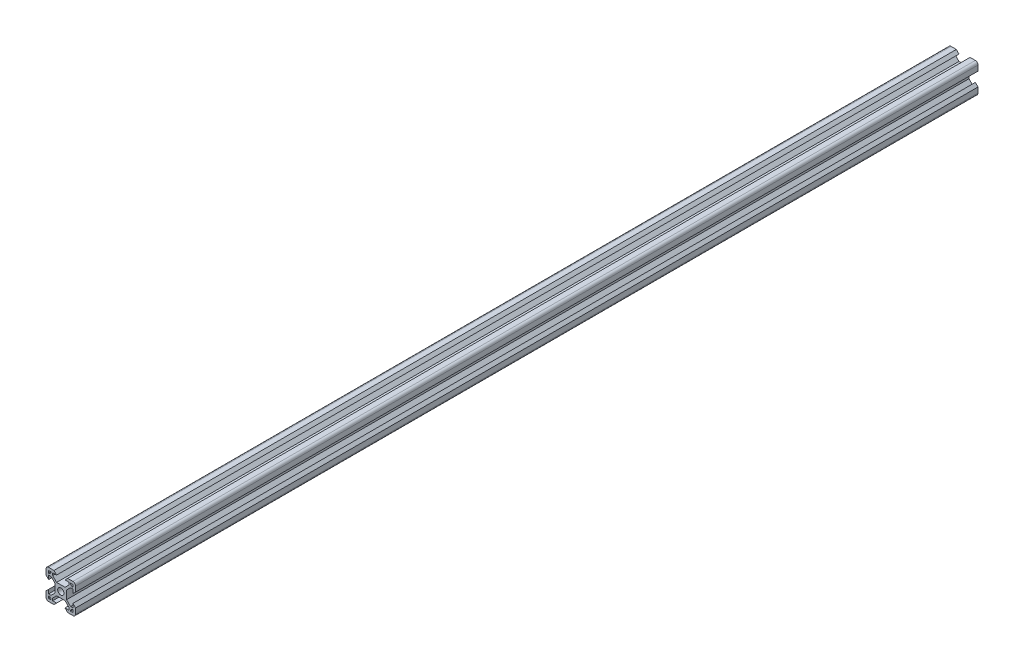
SolidWorks part; units mm, degrees
material "6063-T5"
ref_plane "Plane1" through (0, 0, 0) normal (0, 0, 1) x (1, 0, 0)
ref_plane "Plane2" through (0, 0, 0) normal (0, 1, 0) x (1, 0, 0)
ref_plane "Plane3" through (0, 0, 0) normal (1, 0, 0) x (0, 0, -1)
sketch "Sketch1" plane through (0, 0, 0) normal (0, 0, 1) x (1, 0, 0)
  line L0 (-3.9007, 0) -> (-3.9007, -2.84)
  line L1 (-3.9007, -2.84) -> (-6.56, -5.4993)
  line L2 (-6.56, -5.4993) -> (-8.2, -5.4993)
  line L3 (-8.2, -5.4993) -> (-8.2, -2.84)
  line L4 (-8.2, -2.84) -> (-10, -4.64)
  line L5 (-10, -4.64) -> (-10, -8.2)
  line L6 (0, 0) -> (-17.0509, -17.0509) construction
  line L7 (0, 0) -> (0, -17.0509) construction
  line L8 (0, 0) -> (-30.3777, 0) construction
  line L9 (-4.64, -10) -> (-8.2, -10)
  line L10 (-2.84, -8.2) -> (-4.64, -10)
  line L11 (-5.4993, -8.2) -> (-2.84, -8.2)
  line L12 (-5.4993, -6.56) -> (-5.4993, -8.2)
  line L13 (-2.84, -3.9007) -> (-5.4993, -6.56)
  line L14 (0, -3.9007) -> (-2.84, -3.9007)
  line L15 (-8.2, -8.2) -> (-8.2, -6.5693)
  line L16 (-8.2, -6.5693) -> (-7.63, -6.5693)
  line L17 (-7.63, -6.5693) -> (-6.5693, -7.63)
  line L18 (-6.5693, -7.63) -> (-6.5693, -8.2)
  line L19 (-6.5693, -8.2) -> (-8.2, -8.2)
  line L20 (-3.9007, 0) -> (-3.9007, 2.84)
  line L21 (-3.9007, 2.84) -> (-6.56, 5.4993)
  line L22 (-6.56, 5.4993) -> (-8.2, 5.4993)
  line L23 (-8.2, 5.4993) -> (-8.2, 2.84)
  line L24 (-8.2, 2.84) -> (-10, 4.64)
  line L25 (-10, 4.64) -> (-10, 8.2)
  line L26 (-4.64, 10) -> (-8.2, 10)
  line L27 (-2.84, 8.2) -> (-4.64, 10)
  line L28 (-5.4993, 8.2) -> (-2.84, 8.2)
  line L29 (-5.4993, 6.56) -> (-5.4993, 8.2)
  line L30 (-2.84, 3.9007) -> (-5.4993, 6.56)
  line L31 (0, 3.9007) -> (-2.84, 3.9007)
  line L32 (-8.2, 6.5693) -> (-8.2, 8.2)
  line L33 (-8.2, 8.2) -> (-6.5693, 8.2)
  line L34 (-6.5693, 8.2) -> (-6.5693, 7.63)
  line L35 (-6.5693, 7.63) -> (-7.63, 6.5693)
  line L36 (-7.63, 6.5693) -> (-8.2, 6.5693)
  line L37 (0, 3.9007) -> (2.84, 3.9007)
  line L38 (2.84, 3.9007) -> (5.4993, 6.56)
  line L39 (5.4993, 6.56) -> (5.4993, 8.2)
  line L40 (5.4993, 8.2) -> (2.84, 8.2)
  line L41 (2.84, 8.2) -> (4.64, 10)
  line L42 (4.64, 10) -> (8.2, 10)
  line L43 (10, 4.64) -> (10, 8.2)
  line L44 (8.2, 2.84) -> (10, 4.64)
  line L45 (8.2, 5.4993) -> (8.2, 2.84)
  line L46 (6.56, 5.4993) -> (8.2, 5.4993)
  line L47 (3.9007, 2.84) -> (6.56, 5.4993)
  line L48 (3.9007, 0) -> (3.9007, 2.84)
  line L49 (6.5693, 8.2) -> (8.2, 8.2)
  line L50 (8.2, 8.2) -> (8.2, 6.5693)
  line L51 (8.2, 6.5693) -> (7.63, 6.5693)
  line L52 (7.63, 6.5693) -> (6.5693, 7.63)
  line L53 (6.5693, 7.63) -> (6.5693, 8.2)
  line L54 (3.9007, 0) -> (3.9007, -2.84)
  line L55 (3.9007, -2.84) -> (6.56, -5.4993)
  line L56 (6.56, -5.4993) -> (8.2, -5.4993)
  line L57 (8.2, -5.4993) -> (8.2, -2.84)
  line L58 (8.2, -2.84) -> (10, -4.64)
  line L59 (10, -4.64) -> (10, -8.2)
  line L60 (4.64, -10) -> (8.2, -10)
  line L61 (2.84, -8.2) -> (4.64, -10)
  line L62 (5.4993, -8.2) -> (2.84, -8.2)
  line L63 (5.4993, -6.56) -> (5.4993, -8.2)
  line L64 (2.84, -3.9007) -> (5.4993, -6.56)
  line L65 (0, -3.9007) -> (2.84, -3.9007)
  line L66 (8.2, -6.5693) -> (8.2, -8.2)
  line L67 (8.2, -8.2) -> (6.5693, -8.2)
  line L68 (6.5693, -8.2) -> (6.5693, -7.63)
  line L69 (6.5693, -7.63) -> (7.63, -6.5693)
  line L70 (7.63, -6.5693) -> (8.2, -6.5693)
  circle A0 centre (0, 0) radius 2.1
  arc A1 (-10, -8.2) -> (-8.2, -10) centre (-8.2, -8.2) ccw
  arc A2 (-8.2, 10) -> (-10, 8.2) centre (-8.2, 8.2) ccw
  arc A3 (10, 8.2) -> (8.2, 10) centre (8.2, 8.2) ccw
  arc A4 (8.2, -10) -> (10, -8.2) centre (8.2, -8.2) ccw
  point P23 (-7.0997, -7.0997)
  dimension "D4" = 4.2
  dimension "D1" = 45
  dimension "D2" = 5.68
  dimension "D3" = 1.64
  dimension "D5" = 1.5
  dimension "D6" = 20
  dimension "D7" = 1.8
  dimension "D8" = 1.07
  dimension "D9" = 4
extrude "Extrude1" add sketch "Sketch1" along normal mid plane 609.6
